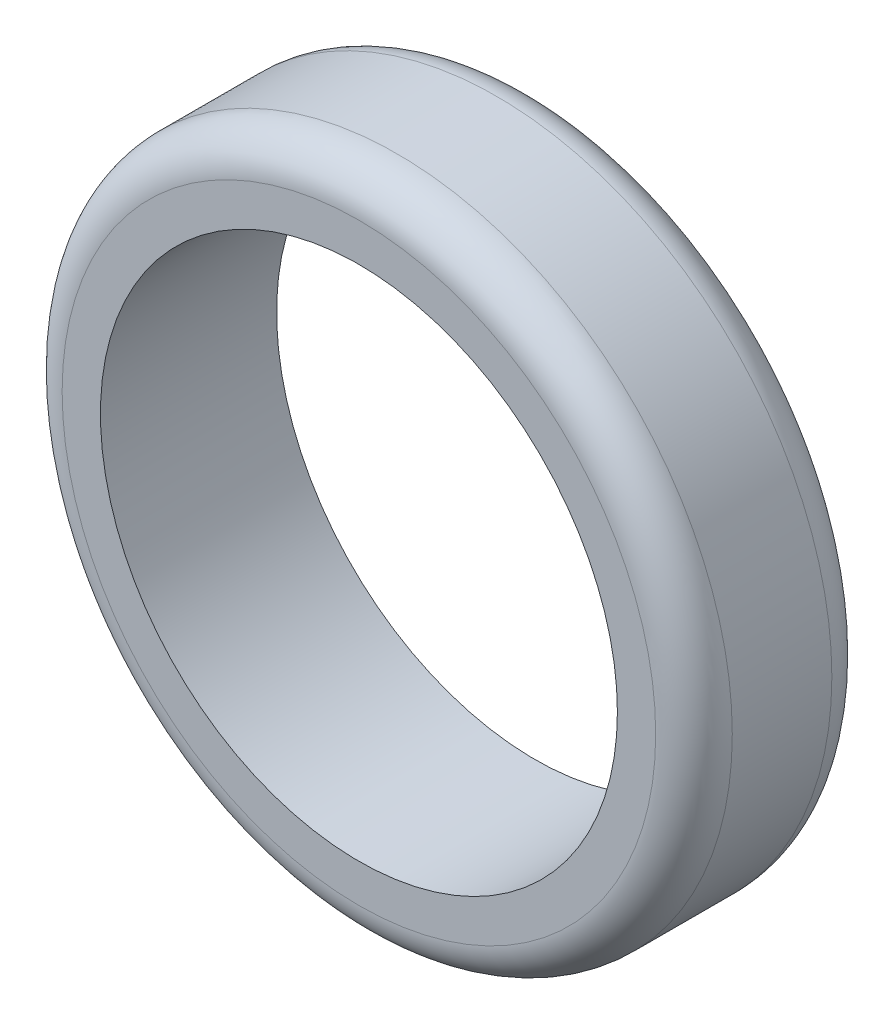
SolidWorks part; units mm, degrees
material "Rubber"
ref_plane "Front Plane" through (0, 0, 0) normal (0, 0, 1) x (1, 0, 0)
ref_plane "Top Plane" through (0, 0, 0) normal (0, 1, 0) x (1, 0, 0)
ref_plane "Right Plane" through (0, 0, 0) normal (1, 0, 0) x (0, 0, -1)
sketch "Sketch1" plane through (0, 0, 0) normal (0, 0, 1) x (1, 0, 0)
  circle A0 centre (0, 0) radius 87.5
  circle A1 centre (0, 0) radius 67.5 construction
  circle A2 centre (0, 0) radius 67.5
  dimension "D1" = 175
extrude "Boss-Extrude1" add sketch "Sketch1" along normal up to surface (46 mm away)
fillet "Fillet1" radius 10 2 edges at (87.5, 0, 46) (87.5, 0, 0)
